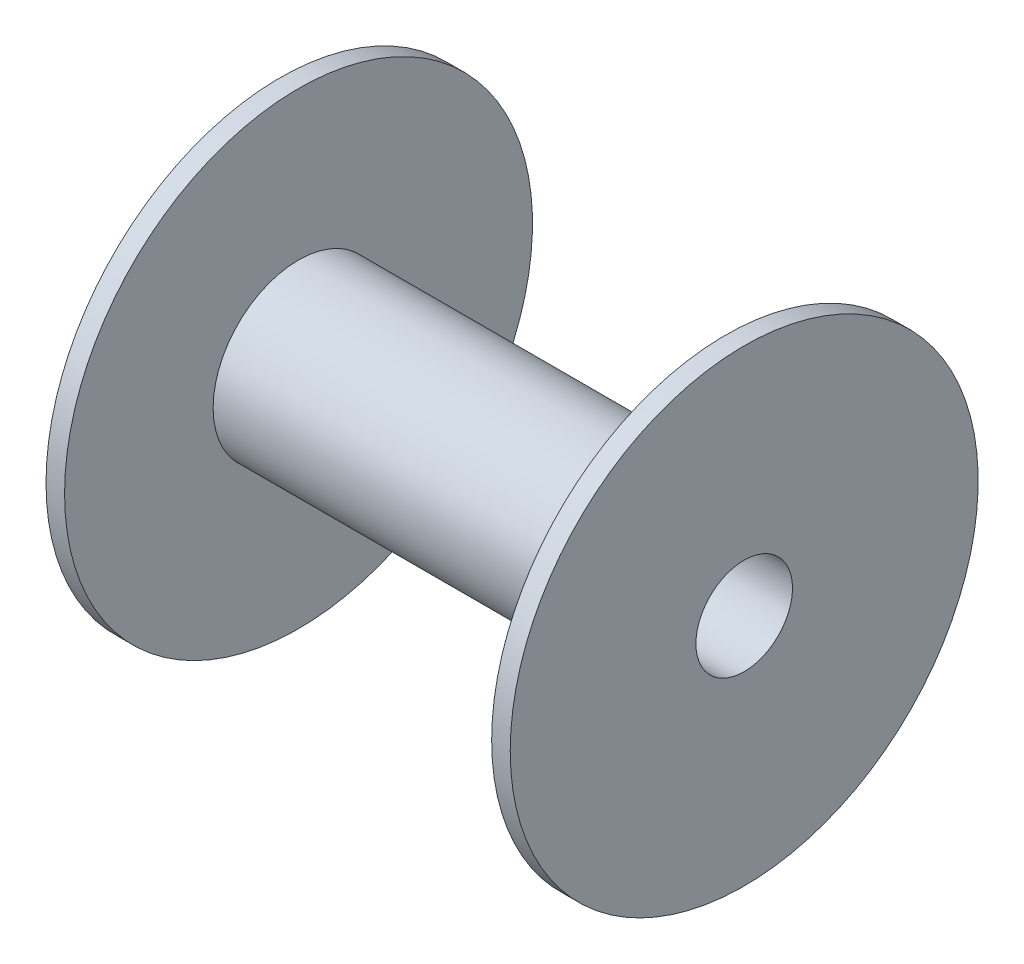
SolidWorks part; units mm, degrees
ref_plane "Front Plane" through (0, 0, 0) normal (0, 0, 1) x (1, 0, 0)
ref_plane "Top Plane" through (0, 0, 0) normal (0, 1, 0) x (1, 0, 0)
ref_plane "Right Plane" through (0, 0, 0) normal (1, 0, 0) x (0, 0, -1)
sketch "Sketch1" plane through (0, 0, 0) normal (0, 0, 1) x (1, 0, 0)
  line L0 (-75, 0) -> (75, 0) construction
  line L2 (-62.5, 63) -> (-57.5, 63)
  line L3 (-57.5, 63) -> (-57.5, 23)
  line L4 (-57.5, 23) -> (57.5, 23)
  line L12 (-62.5, 63) -> (-62.5, 13)
  line L13 (-62.5, 13) -> (62.5, 13)
  line L15 (0, 0) -> (0, 26) construction
  line L16 (62.5, 13) -> (62.5, 63)
  line L17 (62.5, 63) -> (57.5, 63)
  line L18 (57.5, 63) -> (57.5, 23)
  line L19 (75, 0) -> (75, 67.6816) construction
  line L20 (62.5, 13) -> (75, 13) construction
  point P4 (0, 0)
  point P14 (0, 13)
  point P15 (75, 13)
  dimension "D1" = 150
  dimension "D2" = 5
  dimension "D3" = 40
  dimension "D4" = 13
  dimension "D5" = 40
  dimension "D6" = 50
  dimension "D7" = 12.5
  dimension "D8" = 67.6816
  dimension "D9" = 5
revolve "Revolve1" add sketch "Sketch1" angle 360 about L0
